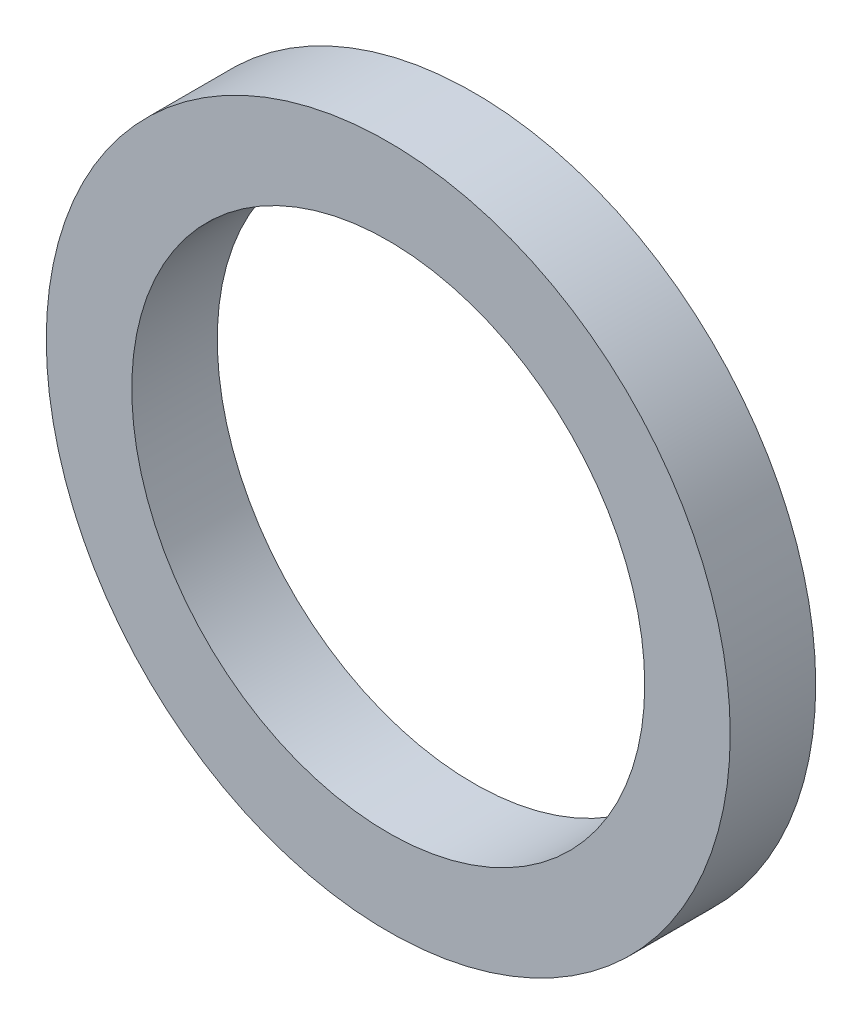
SolidWorks part; units mm, degrees
ref_plane "前视基准面" through (0, 0, 0) normal (0, 0, 1) x (1, 0, 0)
ref_plane "上视基准面" through (0, 0, 0) normal (0, 1, 0) x (1, 0, 0)
ref_plane "右视基准面" through (0, 0, 0) normal (1, 0, 0) x (0, 0, -1)
sketch "草图1" plane through (0, 0, 0) normal (0, 0, 1) x (1, 0, 0)
  circle A0 centre (0, 0) radius 3
  circle A1 centre (0, 0) radius 4
extrude "凸台-拉伸1" add sketch "草图1" along normal blind 1
